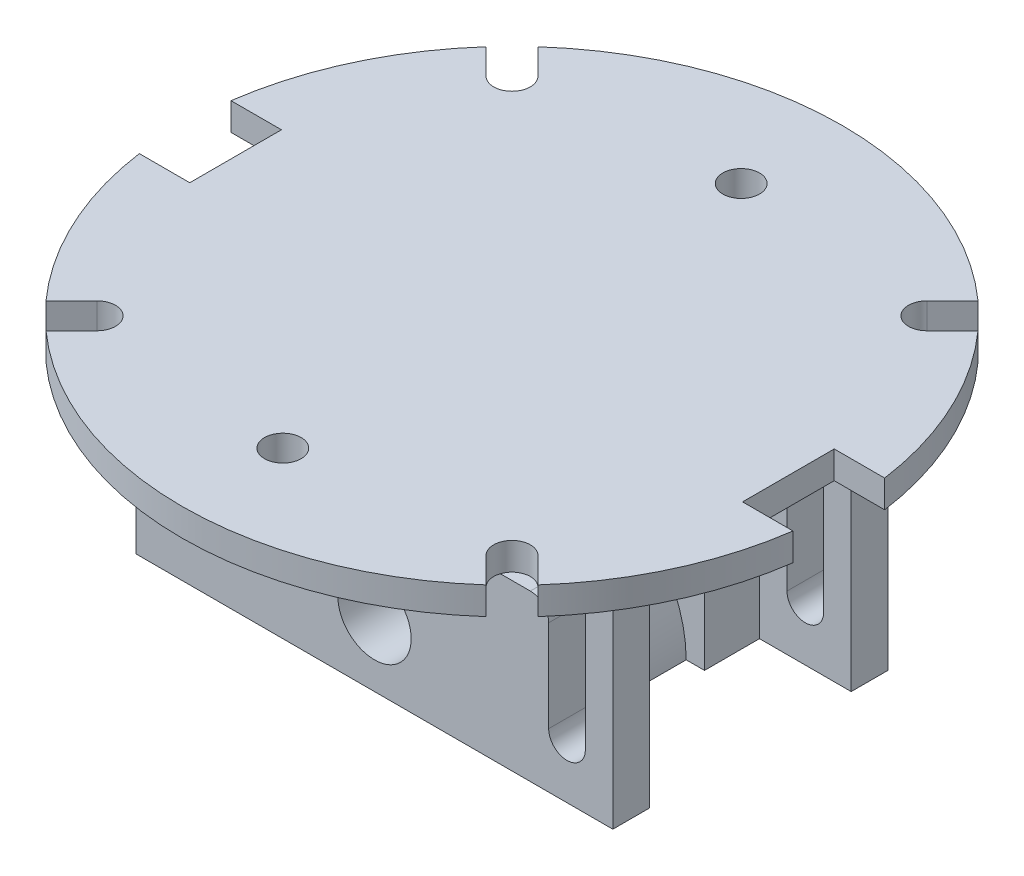
SolidWorks part; units mm, degrees
ref_plane "前视基准面" through (0, 0, 0) normal (0, 0, 1) x (1, 0, 0)
ref_plane "上视基准面" through (0, 0, 0) normal (0, 1, 0) x (1, 0, 0)
ref_plane "右视基准面" through (0, 0, 0) normal (1, 0, 0) x (0, 0, -1)
other "Configuration Table"
sketch "草图1" plane through (0, 0, 0) normal (0, 1, 0) x (1, 0, 0)
  line L0 (13, 5.5) -> (8, 5.5)
  line L1 (-13, 7.5) -> (13, 7.5)
  line L2 (-13, 7.5) -> (-13, 5.5)
  line L3 (-13, -7.5) -> (13, -7.5)
  line L4 (13, 7.5) -> (13, 5.5)
  line L5 (-13, 7.5) -> (13, -7.5) construction
  line L6 (-13, -7.5) -> (13, 7.5) construction
  line L7 (8, 5.5) -> (8, -5.5)
  line L8 (8, -5.5) -> (13, -5.5)
  line L9 (-13, 5.5) -> (-8, 5.5)
  line L10 (-8, 5.5) -> (-8, -5.5)
  line L11 (-8, -5.5) -> (-13, -5.5)
  line L12 (13, -5.5) -> (13, -7.5)
  line L13 (-13, -5.5) -> (-13, -7.5)
  point P0 (0, 0)
  dimension "D1" = 26
  dimension "D2" = 15
  dimension "D3" = 5
  dimension "D4" = 5
  dimension "D5" = 11
  dimension "D6" = 11
  dimension "D7" = 2
extrude "凸台-拉伸1" add sketch "草图1" along normal blind 12.5
sketch "草图2" plane through (0, 0, 0) normal (0, 0, 1) x (1, 0, 0)
  line L0 (0, 0) -> (0, 3.5) construction
  circle A0 centre (0, 3.5) radius 2
  dimension "D2" = 4
  dimension "D1" = 3.5
extrude "切除-拉伸1" cut sketch "草图2" against normal through all and the other way through all
sketch "草图3" plane through (0, 0, 0) normal (0, 0, 1) x (1, 0, 0)
  line L0 (0, 12.5) -> (0, 10) construction
  line L1 (-13, 12.5) -> (13, 12.5) construction
  line L2 (-10.5, 10) -> (-13, 10) construction
  line L3 (-13, 12.5) -> (-13, 0) construction
  line L4 (-10.5, 10) -> (-2, 10) construction
  line L5 (-10.5, 11) -> (-2, 11)
  line L6 (-2, 9) -> (-10.5, 9)
  line L7 (10.5, 10) -> (2, 10) construction
  line L8 (10.5, 10) -> (13, 10) construction
  line L9 (2, 9) -> (10.5, 9)
  line L10 (10.5, 11) -> (2, 11)
  arc A0 (-10.5, 11) -> (-10.5, 9) centre (-10.5, 10) ccw
  arc A1 (-2, 9) -> (-2, 11) centre (-2, 10) ccw
  arc A2 (2, 9) -> (2, 11) centre (2, 10) cw
  arc A3 (10.5, 11) -> (10.5, 9) centre (10.5, 10) cw
  dimension "D2" = 2
  dimension "D6" = 2
  dimension "D1" = 2.5
  dimension "D3" = 2.5
  dimension "D4" = 2.5
  dimension "D5" = 8.5
extrude "切除-拉伸2" cut sketch "草图3" against normal through all and the other way through all
sketch "草图5" plane through (0, 0, 0) normal (0, 1, 0) x (1, 0, 0)
  line L0 (8, -5.5) -> (8, 5.5) construction
  line L1 (-8, 2.5) -> (8, 2.5)
  line L2 (-8, 2.5) -> (-8, -2.5)
  line L3 (-8, -2.5) -> (8, -2.5)
  line L4 (8, 2.5) -> (8, -2.5)
  line L5 (-8, 2.5) -> (8, -2.5) construction
  line L6 (-8, -2.5) -> (8, 2.5) construction
  point P0 (0, 0)
  dimension "D1" = 5
extrude "切除-拉伸4" cut sketch "草图5" against normal blind 5.5 from surface at 12.5 starting at face at (0, 12.5, 0)
sketch "草图6" plane through (0, 0, 0) normal (0, 0, 1) x (1, 0, 0)
  line L0 (-8, 0) -> (-8, 7)
  line L1 (-8, 9) -> (-8, 0) construction
  line L2 (-8, 7) -> (8, 7)
  line L3 (8, 7) -> (8, 0)
  line L4 (8, 0) -> (13, 0) construction
  line L5 (8, 9) -> (8, 0) construction
  line L6 (8, 0) -> (7, 0)
  line L7 (-8, 0) -> (-7, 0)
  arc A0 (7, 0) -> (-7, 0) centre (0, 0) ccw
  dimension "D1" = 14
  dimension "D2" = 7
extrude "切除-拉伸5" cut sketch "草图6" against normal blind 2.5 and the other way blind 2.5 contours A0 L6 L3 L2 | A0 L2 L0 L7
sketch "草图7" plane through (0, 0, 0) normal (0, 1, 0) x (1, 0, 0)
  line L0 (-1000, 0) -> (49000, 0) construction
  line L2 (17.8255, 2.5) -> (15.0755, 2.5)
  line L3 (15.0755, -2.5) -> (17.8255, -2.5)
  line L4 (15.0755, 2.5) -> (15.0755, -2.5)
  line L5 (0, -1000) -> (0, 49000) construction
  line L6 (-15.0755, 2.5) -> (-15.0755, -2.5)
  line L7 (-15.0755, -2.5) -> (-17.8255, -2.5)
  line L8 (-17.8255, 2.5) -> (-15.0755, 2.5)
  arc A0 (17.8255, 2.5) -> (-17.8255, 2.5) centre (0, 0) ccw
  arc A1 (-17.8255, -2.5) -> (17.8255, -2.5) centre (0, 0) ccw
  point P8 (17.8255, 0)
  dimension "D1" = 36
  dimension "D2" = 5
  dimension "D3" = 2.75
  dimension "D4" = 2.75
extrude "凸台-拉伸5" add sketch "草图7" along normal blind 1.5 from surface at 12.5 starting at face at (0, 12.5, -5.25)
ref_plane "基准面1" through (0, 0, -2.5) normal (0, 0, 1) x (1, 0, 0)
ref_plane "基准面2" through (0, 0, 2.5) normal (0, 0, -1) x (-1, 0, 0)
sketch "草图8" plane through (0, 0, 0) normal (0, 1, 0) x (1, 0, 0)
  line L0 (0, 12.5) -> (0, -12.5) construction
  circle A0 centre (0, 12.5) radius 1
  circle A1 centre (0, -12.5) radius 1
  point P4 (0, 0)
  dimension "D2" = 2
  dimension "D3" = 2
  dimension "D1" = 25
extrude "切除-拉伸6" cut sketch "草图8" against normal up to next from surface
sketch "草图9" plane through (0, 0, 0) normal (0, 1, 0) x (1, 0, 0)
  line L0 (-707.1068, -707.1068) -> (34648.2323, 34648.2323) construction
  line L1 (707.1068, -707.1068) -> (-34648.2323, 34648.2323) construction
  line L2 (-11.3137, 11.3137) -> (-12.7279, 12.7279) construction
  line L3 (-12.0208, 10.6066) -> (-13.435, 12.0208)
  line L4 (-10.6066, 12.0208) -> (-12.0208, 13.435)
  line L5 (11.3137, -11.3137) -> (12.7279, -12.7279) construction
  line L6 (10.6066, -12.0208) -> (12.0208, -13.435)
  line L7 (12.0208, -10.6066) -> (13.435, -12.0208)
  line L8 (-1000, 0) -> (49000, 0) construction
  line L9 (-11.3137, -11.3137) -> (-12.7279, -12.7279) construction
  line L10 (-12.0208, -10.6066) -> (-13.435, -12.0208)
  line L11 (-10.6066, -12.0208) -> (-12.0208, -13.435)
  line L12 (11.3137, 11.3137) -> (12.7279, 12.7279) construction
  line L13 (10.6066, 12.0208) -> (12.0208, 13.435)
  line L14 (12.0208, 10.6066) -> (13.435, 12.0208)
  arc A0 (-12.0208, 10.6066) -> (-10.6066, 12.0208) centre (-11.3137, 11.3137) ccw
  arc A1 (-12.0208, 13.435) -> (-13.435, 12.0208) centre (-12.7279, 12.7279) ccw
  arc A2 (10.6066, -12.0208) -> (12.0208, -10.6066) centre (11.3137, -11.3137) cw
  arc A3 (13.435, -12.0208) -> (12.0208, -13.435) centre (12.7279, -12.7279) cw
  arc A4 (-12.0208, -10.6066) -> (-10.6066, -12.0208) centre (-11.3137, -11.3137) cw
  arc A5 (-12.0208, -13.435) -> (-13.435, -12.0208) centre (-12.7279, -12.7279) cw
  arc A6 (10.6066, 12.0208) -> (12.0208, 10.6066) centre (11.3137, 11.3137) ccw
  arc A7 (13.435, 12.0208) -> (12.0208, 13.435) centre (12.7279, 12.7279) ccw
  point P7 (-12.0208, 12.0208)
  point P12 (-12.7279, 11.3137)
  point P15 (12.0208, -12.0208)
  point P24 (-12.0208, -12.0208)
  point P31 (12.0208, 12.0208)
  dimension "D1" = 2
  dimension "D2" = 2
  dimension "D3" = 17
extrude "切除-拉伸7" cut sketch "草图9" against normal up to surface (1.5 mm away) from surface at 14 up to face at (0, 12.5, -11.5) starting at face at (0, 14, -11.5)
sketch "草图10" plane through (0, 0, 0) normal (0, 0, 1) x (1, 0, 0)
  line L0 (-11.5, 10) -> (-11.5, 3)
  line L1 (-9.5, 3) -> (-9.5, 10)
  line L2 (0, -1000) -> (0, 49000) construction
  line L3 (11.5, 10) -> (11.5, 3)
  line L4 (9.5, 3) -> (9.5, 10)
  arc A0 (-9.5, 10) -> (-11.5, 10) centre (-10.5, 10) ccw
  arc A1 (-11.5, 3) -> (-9.5, 3) centre (-10.5, 3) ccw
  arc A2 (11.5, 3) -> (9.5, 3) centre (10.5, 3) cw
  arc A3 (9.5, 10) -> (11.5, 10) centre (10.5, 10) cw
  dimension "D1" = 2
  dimension "D2" = 7
extrude "切除-拉伸9" cut sketch "草图10" against normal through all and the other way through all
sketch "草图11" plane through (0, 0, 0) normal (0, 0, 1) x (1, 0, 0)
  line L0 (9.5, 3) -> (9.5, 9) construction
  line L1 (2, 9) -> (9.5, 9) construction
  line L2 (0, -1000) -> (0, 49000) construction
  line L3 (8.5, 9) -> (9.5, 9)
  line L4 (9.5, 9) -> (9.5, 8)
  line L5 (-9.5, 9) -> (-9.5, 8)
  line L6 (-8.5, 9) -> (-9.5, 9)
  arc A0 (9.5, 8) -> (8.5, 9) centre (8.5, 8) ccw
  arc A1 (-9.5, 8) -> (-8.5, 9) centre (-8.5, 8) cw
  dimension "D1" = 2
extrude "切除-拉伸10" cut sketch "草图11" against normal through all and the other way through all
equation "\"2、\"=8"
